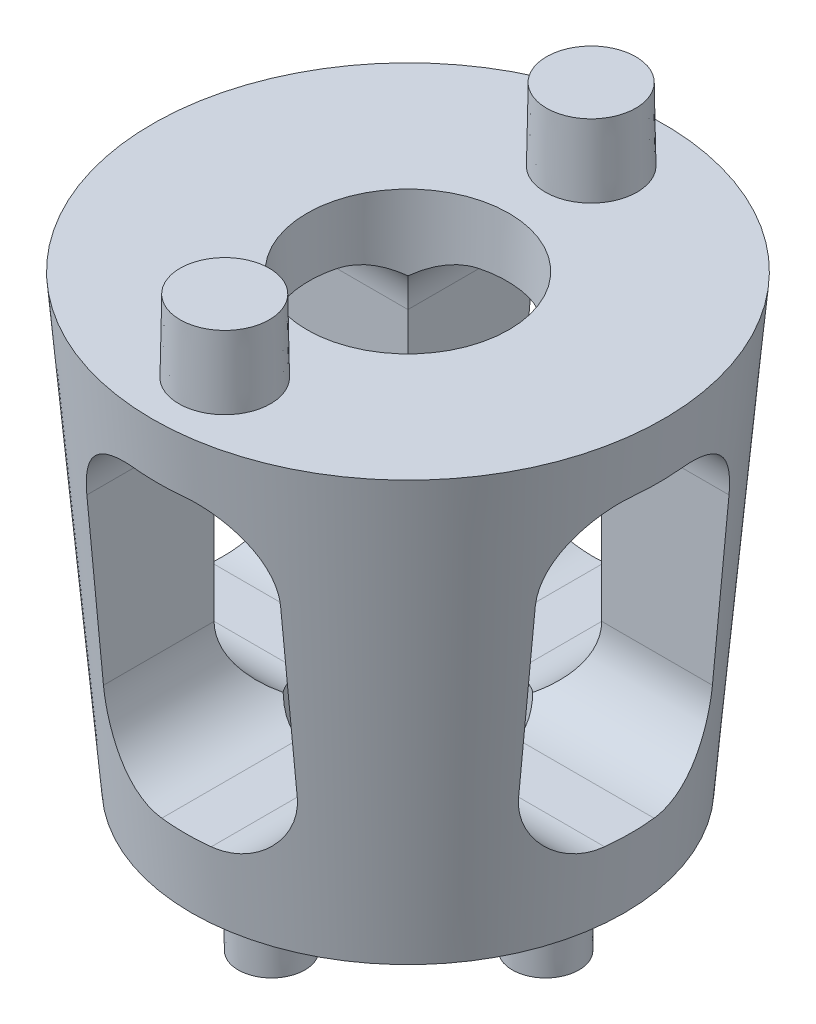
SolidWorks part; units mm, degrees
ref_plane "前视基准面" through (0, 0, 0) normal (0, 0, 1) x (1, 0, 0)
ref_plane "上视基准面" through (0, 0, 0) normal (0, 1, 0) x (1, 0, 0)
ref_plane "右视基准面" through (0, 0, 0) normal (1, 0, 0) x (0, 0, -1)
other "Configuration Table"
sketch "草图1" plane through (0, 0, 0) normal (0, 1, 0) x (1, 0, 0)
  circle A0 centre (0, 0) radius 15.004
  dimension "D1" = 30.008
extrude "凸台-拉伸1" add sketch "草图1" along normal blind 31 draft 5 draft outward yes
sketch "草图5" plane through (0, 31, 0) normal (0, 1, 0) x (1, 0, 0)
  circle A0 centre (-12.7, 0) radius 3.18
  circle A1 centre (0, 12.7) radius 3.18
  circle A2 centre (12.7, 0) radius 3.18
  circle A3 centre (0, -12.7) radius 3.18
  point P12 (0, 0)
  dimension "D1" = 12.7
  dimension "D2" = 4
extrude "凸台-拉伸4" add sketch "草图5" along normal blind 5 draft 1
sketch "草图6" plane through (0, 0, 0) normal (0, -1, 0) x (1, 0, 0)
  circle A0 centre (-9.4524, 0) radius 2.4
  circle A1 centre (0.0476, 9.5) radius 2.4
  circle A2 centre (9.5476, 0) radius 2.4
  circle A3 centre (0.0476, -9.5) radius 2.4
  point P11 (0.0476, 0)
  dimension "D1" = 4
  dimension "D2" = 9.5
extrude "凸台-拉伸5" add sketch "草图6" along normal blind 5 draft 1
sketch "草图7" plane through (0, 31, 0) normal (0, 1, 0) x (1, 0, 0)
  circle A0 centre (0, 0) radius 7
extrude "切除-拉伸2" cut sketch "草图7" against normal blind 40 draft 2
sketch "草图8" plane through (0, 0, 0) normal (1, 0, 0) x (0, 0, -1)
  line L0 (-17.7161, 31) -> (-17.7161, 0.667) construction
  line L1 (-1.7161, 27) -> (1.7161, 27)
  line L2 (-6.7161, 22) -> (-6.7161, 10)
  line L3 (-1.7161, 5) -> (1.7161, 5)
  line L4 (6.7161, 22) -> (6.7161, 10)
  line L5 (17.7161, 31) -> (17.7161, 0.667) construction
  line L7 (17.7161, 31) -> (-17.7161, 31) construction
  line L8 (-15.004, 0) -> (15.004, 0) construction
  arc A0 (-6.7161, 10) -> (-1.7161, 5) centre (-1.7161, 10) ccw
  arc A1 (1.7161, 5) -> (6.7161, 10) centre (1.7161, 10) ccw
  arc A2 (1.7161, 27) -> (6.7161, 22) centre (1.7161, 22) cw
  arc A3 (-1.7161, 27) -> (-6.7161, 22) centre (-1.7161, 22) ccw
  dimension "D5" = 5
  dimension "D1" = 11
  dimension "D2" = 11
  dimension "D3" = 4
  dimension "D4" = 5
extrude "切除-拉伸3" cut sketch "草图8" against normal mid plane 40
pattern_circular "阵列(圆周)1" count 4 over 360 about axis through (0, 0, 0) along (0, 1, 0) of "切除-拉伸3"
sketch "草图9" plane through (0, 0, 0) normal (1, 0, 0) x (0, 0, -1)
  line L0 (7, 31) -> (-7, 31) construction
  line L1 (-4.1204, 31) -> (4.4932, 31)
  line L2 (-4.1204, 31) -> (-4.1204, 40.2357)
  line L3 (-4.1204, 40.2357) -> (4.4932, 40.2357)
  line L4 (4.4932, 31) -> (4.4932, 40.2357)
extrude "切除-拉伸4" cut sketch "草图9" against normal mid plane 50
